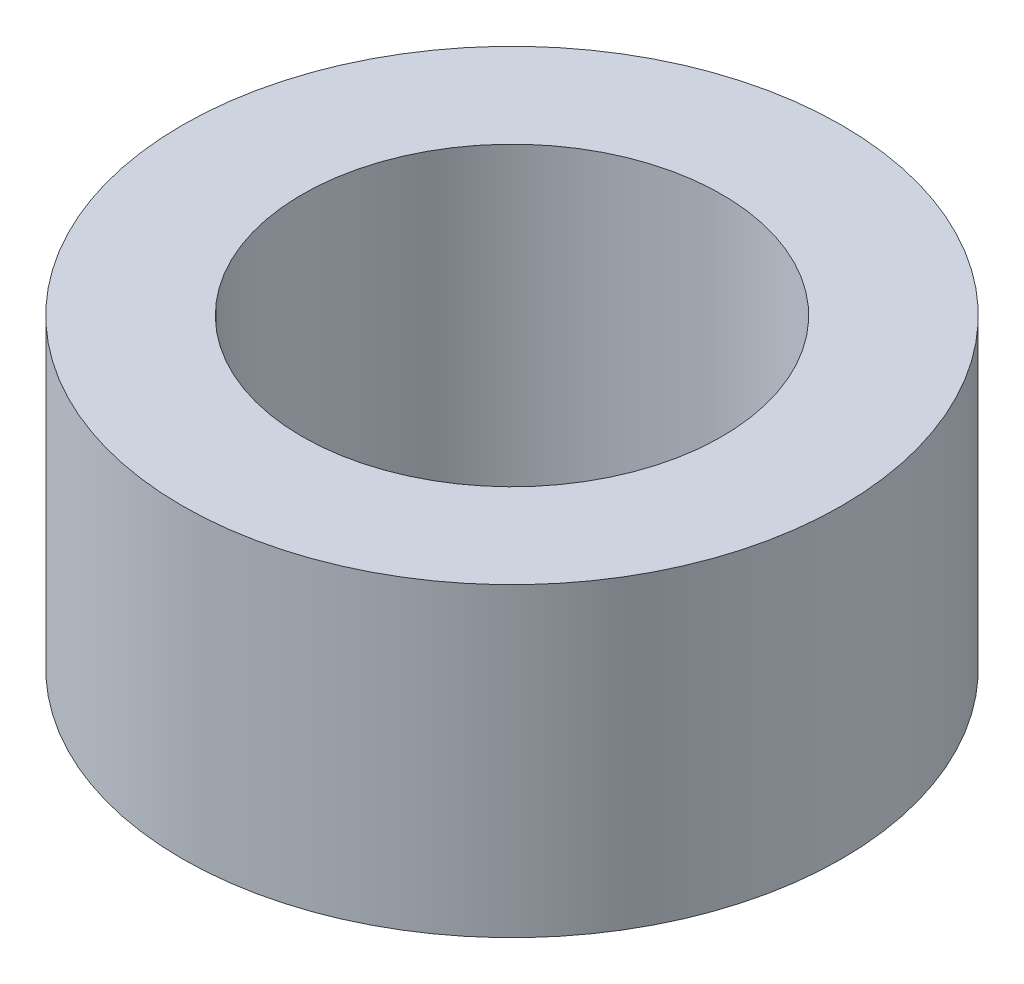
SolidWorks part; units mm, degrees
ref_plane "前视基准面" through (0, 0, 0) normal (0, 0, 1) x (1, 0, 0)
ref_plane "上视基准面" through (0, 0, 0) normal (0, 1, 0) x (1, 0, 0)
ref_plane "右视基准面" through (0, 0, 0) normal (1, 0, 0) x (0, 0, -1)
other "Configuration Table"
sketch "草图1" plane through (0, 0, 0) normal (0, 1, 0) x (1, 0, 0)
  circle A0 centre (0, 0) radius 3.5
  circle A1 centre (0, 0) radius 5.5
  dimension "D1" = 11
  dimension "D2" = 7
extrude "凸台-拉伸1" add sketch "草图1" along normal blind 5.1
